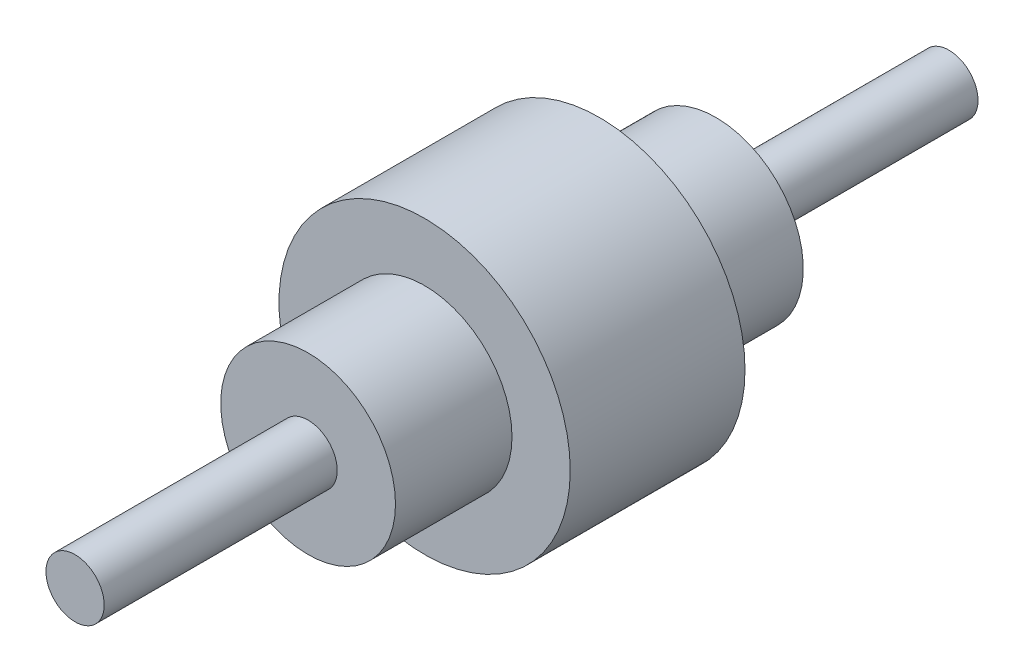
SolidWorks part; units mm, degrees
ref_plane "Front Plane" through (0, 0, 0) normal (0, 0, 1) x (1, 0, 0)
ref_plane "Top Plane" through (0, 0, 0) normal (0, 1, 0) x (1, 0, 0)
ref_plane "Right Plane" through (0, 0, 0) normal (1, 0, 0) x (0, 0, -1)
sketch "Sketch1" plane through (0, 0, 0) normal (0, 0, 1) x (1, 0, 0)
  circle A0 centre (0, 0) radius 1270
  dimension "D1" = 2540
extrude "Boss-Extrude1" add sketch "Sketch1" along normal blind 1524
sketch "Sketch2" plane through (0, 0, 1524) normal (0, 0, 1) x (1, 0, 0)
  circle A0 centre (0, 0) radius 762
  dimension "D1" = 1524
extrude "Boss-Extrude2" add sketch "Sketch2" along normal blind 1016
sketch "Sketch3" plane through (0, 0, 2540) normal (0, 0, 1) x (1, 0, 0)
  circle A0 centre (0, 0) radius 254
  dimension "D1" = 508
extrude "Boss-Extrude3" add sketch "Sketch3" along normal blind 2032
sketch "Sketch4" plane through (0, 0, 0) normal (0, 0, -1) x (-1, 0, 0)
  circle A0 centre (0, 0) radius 762
  dimension "D1" = 1524
extrude "Boss-Extrude4" add sketch "Sketch4" along normal blind 1016
sketch "Sketch5" plane through (0, 0, -1016) normal (0, 0, -1) x (-1, 0, 0)
  circle A0 centre (0, 0) radius 254
  dimension "D1" = 508
extrude "Boss-Extrude5" add sketch "Sketch5" along normal blind 2032
